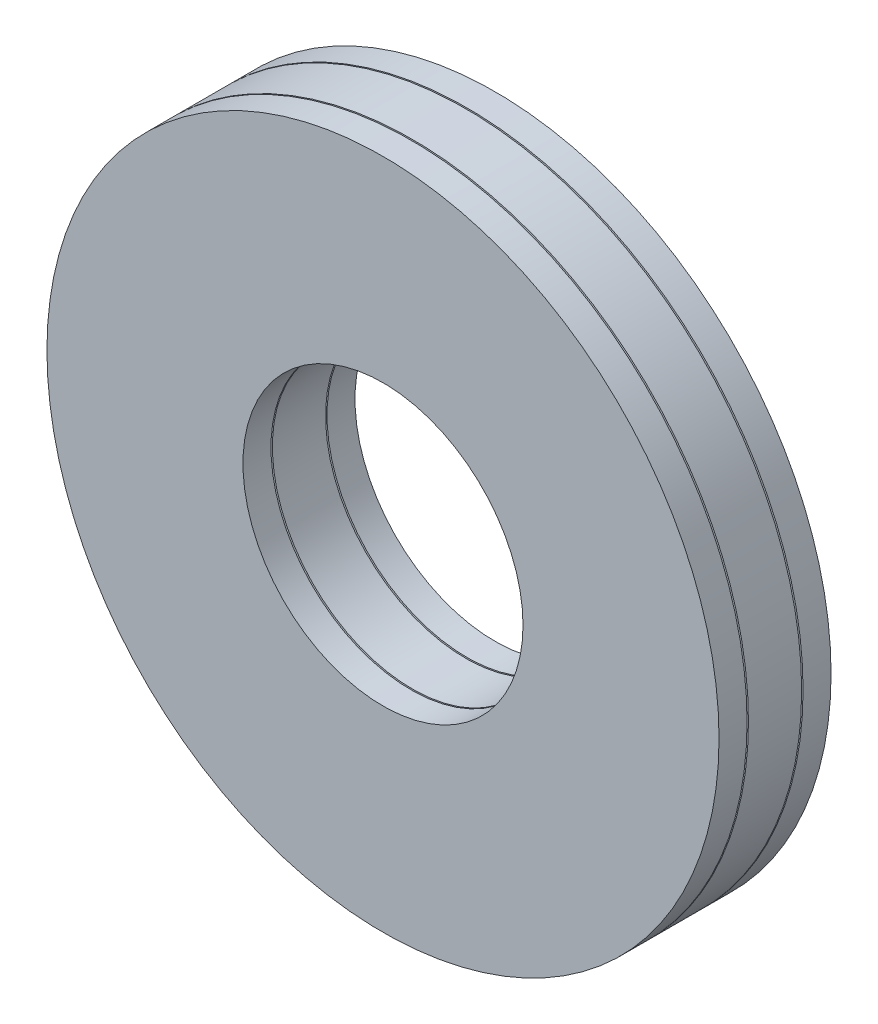
SolidWorks part; units mm, degrees
ref_plane "前视基准面" through (0, 0, 0) normal (0, 0, 1) x (1, 0, 0)
ref_plane "上视基准面" through (0, 0, 0) normal (0, 1, 0) x (1, 0, 0)
ref_plane "右视基准面" through (0, 0, 0) normal (1, 0, 0) x (0, 0, -1)
sketch "草图1" plane through (0, 0, 0) normal (1, 0, 0) x (0, 0, -1)
  line L0 (-2, 0) -> (2, 0) construction
  line L1 (0, 12) -> (0, -12) construction
  line L2 (0.95, 12) -> (-0.95, 12)
  line L3 (-0.95, 12) -> (-0.95, 11.5)
  line L4 (-0.95, 11.5) -> (-1, 11.5)
  line L5 (-1, 11.5) -> (-1, 6)
  line L6 (-1, 6) -> (-0.95, 6)
  line L7 (-0.95, 6) -> (-0.95, 5)
  line L8 (-0.95, 5) -> (0.95, 5)
  line L9 (0.95, 6) -> (0.95, 5)
  line L10 (1, 6) -> (0.95, 6)
  line L11 (1, 11.5) -> (1, 6)
  line L12 (0.95, 11.5) -> (1, 11.5)
  line L13 (0.95, 12) -> (0.95, 11.5)
  line L15 (1, 12) -> (2, 12)
  line L16 (1, 12) -> (1, 5)
  line L17 (1, 5) -> (2, 5)
  line L18 (2, 12) -> (2, 5)
  dimension "D1" = 24
  dimension "A" = 2
  dimension "D2" = 1.9
  dimension "D" = 24
  dimension "(d)" = 10
  dimension "E1" = 12
  dimension "E" = 23
  dimension "B" = 1
  dimension "(d1)" = 10
sketch "草图2" plane through (0, 0, 0) normal (1, 0, 0) x (0, 0, -1)
  line L0 (1, 12) -> (2, 12) construction
  line L2 (1, 5) -> (2, 5) construction
  line L3 (2, 12) -> (2, 5) construction
  line L4 (0.95, 12) -> (-0.95, 12) construction
  line L5 (-0.95, 12) -> (-0.95, 11.5) construction
  line L6 (-0.95, 11.5) -> (-1, 11.5) construction
  line L8 (-1, 6) -> (-0.95, 6) construction
  line L9 (-0.95, 6) -> (-0.95, 5) construction
  line L10 (-0.95, 5) -> (0.95, 5) construction
  line L11 (0.95, 6) -> (0.95, 5) construction
  line L12 (1, 6) -> (0.95, 6) construction
  line L14 (0.95, 11.5) -> (1, 11.5) construction
  line L15 (0.95, 12) -> (0.95, 11.5) construction
  line L16 (1, 12) -> (2, 12)
  line L17 (1, 12) -> (1, 5) construction
  line L18 (1, 5) -> (2, 5)
  line L19 (2, 12) -> (2, 5)
  line L20 (0.95, 12) -> (-0.95, 12)
  line L21 (-0.95, 12) -> (-0.95, 11.5)
  line L22 (-0.95, 11.5) -> (-1, 11.5)
  line L23 (-2, 12) -> (-2, 5)
  line L24 (-1, 6) -> (-0.95, 6)
  line L25 (-0.95, 6) -> (-0.95, 5)
  line L26 (-0.95, 5) -> (0.95, 5)
  line L27 (0.95, 6) -> (0.95, 5)
  line L28 (1, 6) -> (0.95, 6)
  line L29 (1, 12) -> (1, 11.5)
  line L30 (0.95, 11.5) -> (1, 11.5)
  line L31 (0.95, 12) -> (0.95, 11.5)
  line L32 (1, 6) -> (1, 5)
  line L33 (0, 12) -> (0, -12) construction
  line L34 (0, 12) -> (0, -12) construction
  line L35 (-1, 5) -> (-2, 5)
  line L36 (-1, 12) -> (-2, 12)
  line L37 (-1, 6) -> (-1, 5)
  line L38 (-1, 12) -> (-1, 11.5)
revolve "旋转1" add sketch "草图2" angle 360 mid plane about L0
